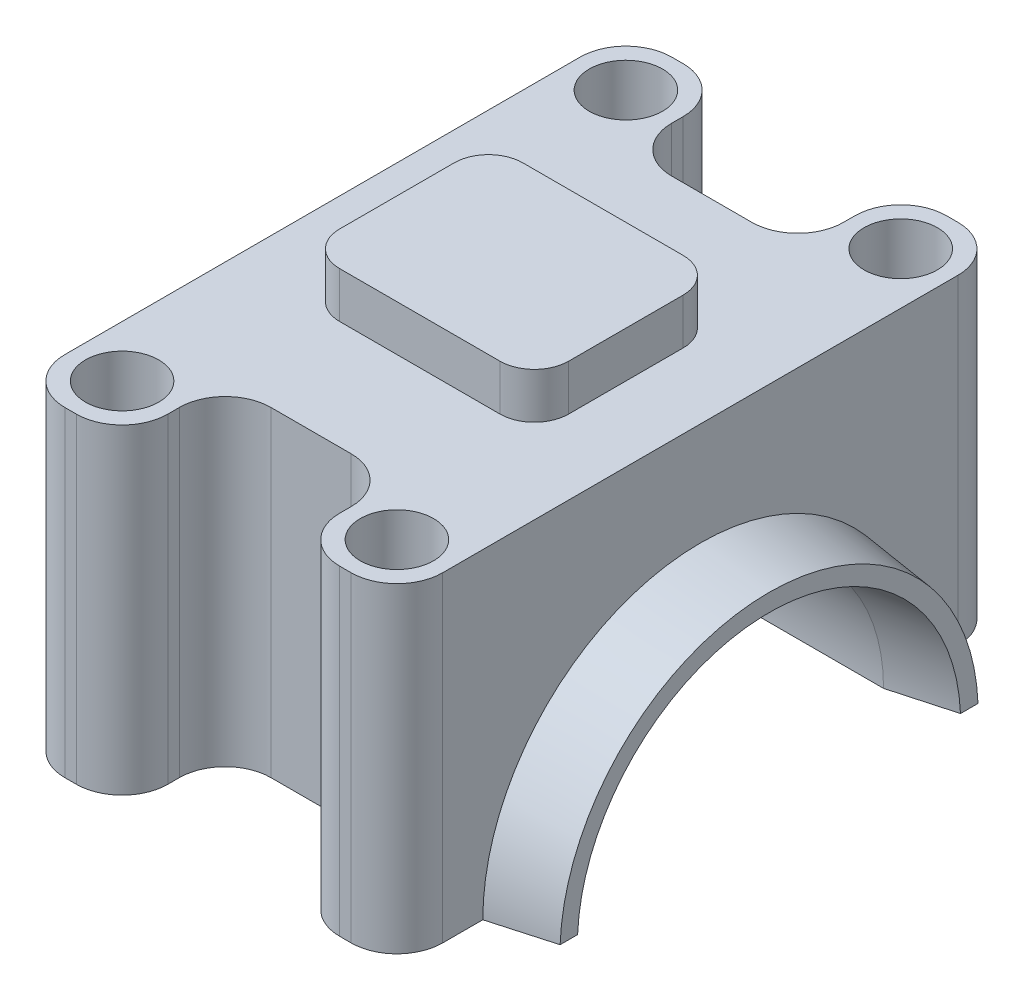
SolidWorks part; units mm, degrees
ref_plane "Front Plane" through (0, 0, 0) normal (0, 0, 1) x (1, 0, 0)
ref_plane "Top Plane" through (0, 0, 0) normal (0, 1, 0) x (1, 0, 0)
ref_plane "Right Plane" through (0, 0, 0) normal (1, 0, 0) x (0, 0, -1)
sketch "Sketch1" plane through (0, 0, 0) normal (0, 1, 0) x (1, 0, 0)
  line L0 (-8.25, 0) -> (-8.25, 13.25)
  line L1 (-8.25, 13.25) -> (-3.75, 13.25)
  line L2 (-3.75, 13.25) -> (-3.75, 8.75)
  line L3 (3.75, 8.75) -> (-3.75, 8.75)
  line L4 (0, -7.8369) -> (0, 20.5603) construction
  line L5 (3.75, 13.25) -> (3.75, 8.75)
  line L6 (8.25, 13.25) -> (3.75, 13.25)
  line L7 (8.25, 0) -> (8.25, 13.25)
  line L8 (-8.25, 0) -> (8.25, 0)
  point P10 (0, 8.75)
  dimension "D1" = 13.25
  dimension "D2" = 16.5
  dimension "D3" = 4.5
  dimension "D4" = 4.5
extrude "Boss-Extrude1" add sketch "Sketch1" along normal blind 14
sketch "Sketch2" plane through (0, 14, 0) normal (0, 1, 0) x (1, 0, 0)
  line L0 (-3.75, 8.75) -> (-3.75, 13.25) construction
  line L3 (-6, 13.25) -> (-6, 0) construction
  line L4 (-3.75, 13.25) -> (-8.25, 13.25) construction
  line L5 (-8.25, 0) -> (8.25, 0) construction
  line L7 (-3.75, 11) -> (-8.25, 11) construction
  line L8 (-8.25, 13.25) -> (-8.25, 0) construction
  line L9 (3.75, 11) -> (8.25, 11) construction
  line L10 (3.75, 13.25) -> (3.75, 8.75) construction
  line L11 (8.25, 0) -> (8.25, 13.25) construction
  line L12 (6, 13.25) -> (6, 0) construction
  line L13 (8.25, 13.25) -> (3.75, 13.25) construction
  circle A0 centre (-6, 11) radius 1.6
  circle A1 centre (6, 11) radius 1.6
  dimension "D1" = 3.2
  dimension "D2" = 3.2
extrude "Cut-Extrude1" cut sketch "Sketch2" against normal up to next
fillet "Fillet2" radius 2 6 edges at (8.25, 7, -13.25) (3.75, 7, -13.25) (3.75, 7, -8.75) (-3.75, 7, -8.75) (-3.75, 7, -13.25) (-8.25, 7, -13.25)
mirror "Mirror1" about plane through (0, 0, 0) normal (0, 0, 1) of "Boss-Extrude1", "Cut-Extrude1", "Fillet2"
sketch "Sketch3" plane through (0, 14, 0) normal (0, 1, 0) x (1, 0, 0)
  line L1 (-3.5, -4) -> (3.5, -4)
  line L2 (-5, -2.5) -> (-5, 2.5)
  line L3 (-3.5, 4) -> (3.5, 4)
  line L4 (5, -2.5) -> (5, 2.5)
  line L5 (-5, -4) -> (5, 4) construction
  line L6 (-5, 4) -> (5, -4) construction
  arc A0 (-3.5, -4) -> (-5, -2.5) centre (-3.5, -2.5) cw
  arc A1 (3.5, -4) -> (5, -2.5) centre (3.5, -2.5) ccw
  arc A2 (3.5, 4) -> (5, 2.5) centre (3.5, 2.5) cw
  arc A3 (-5, 2.5) -> (-3.5, 4) centre (-3.5, 2.5) cw
  point P0 (0, 0)
  dimension "D3" = 1.5
  dimension "D1" = 10
  dimension "D2" = 8
extrude "Boss-Extrude2" add sketch "Sketch3" along normal blind 2
sketch "Sketch4" plane through (8.25, 0, 0) normal (1, 0, 0) x (0, 0, -1)
  line L0 (-11.25, 0) -> (11.25, 0) construction
  line L1 (-8, 0) -> (8, 0)
  arc A0 (-8, 0) -> (8, 0) centre (0, 0) cw
  dimension "D1" = 16
extrude "Cut-Extrude2" cut sketch "Sketch4" against normal up to next
sketch "Sketch5" plane through (8.25, 0, 0) normal (1, 0, 0) x (0, 0, -1)
  line L0 (-11.25, 0) -> (-8, 0) construction
  line L1 (8, 0) -> (11.25, 0) construction
  line L2 (-9.5, 0) -> (-8, 0)
  line L3 (8, 0) -> (9.5, 0)
  arc A0 (-9.5, 0) -> (9.5, 0) centre (0, 0) cw
  arc A1 (-8, 0) -> (8, 0) centre (0, 0) cw
  dimension "D1" = 1.5
extrude "Boss-Extrude3" add sketch "Sketch5" along normal blind 3 draft 7
sketch "Sketch6" plane through (-8.25, 0, 0) normal (-1, 0, 0) x (0, 0, 1)
  line L0 (-11.25, 0) -> (-8, 0) construction
  line L1 (8, 0) -> (11.25, 0) construction
  line L2 (-9.5, 0) -> (-8, 0)
  line L3 (8, 0) -> (9.5, 0)
  arc A0 (-9.5, 0) -> (9.5, 0) centre (0, 0) cw
  arc A1 (-8, 0) -> (8, 0) centre (0, 0) cw
  dimension "D1" = 1.5
extrude "Boss-Extrude4" add sketch "Sketch6" along normal blind 1.5
